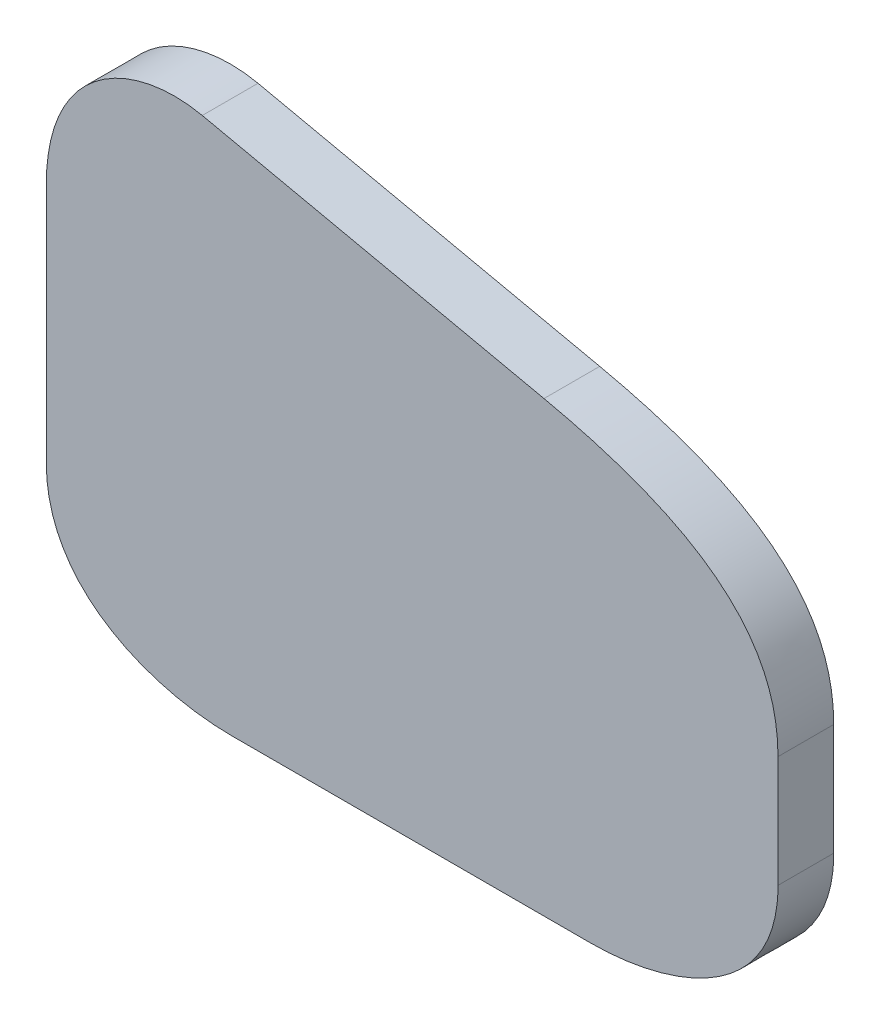
SolidWorks part; units mm, degrees
ref_plane "Спереди" through (0, 0, 0) normal (0, 0, 1) x (1, 0, 0)
ref_plane "Сверху" through (0, 0, 0) normal (0, 1, 0) x (1, 0, 0)
ref_plane "Справа" through (0, 0, 0) normal (1, 0, 0) x (0, 0, -1)
sketch "Эскиз1_fr" plane through (0, 0, 0) normal (0, 0, 1) x (1, 0, 0)
  line L0 (0, 0) -> (0, 20)
  line L1 (-41.9869, 54.6497) -> (-103.3012, 67.9789)
  line L2 (-131.2925, 43.0977) -> (-131.2925, 0)
  line L3 (-33.5451, -25.7698) -> (-97.9695, -25.7698)
  spline S0 degree 3 poles (0, 20) (0, 38.146) (-14.2095, 48.6111) (-41.9869, 54.6497) knots 0 0 0 0 1 1 1 1
  spline S1 degree 3 poles (-103.3012, 67.9789) (-115.5, 70.6308) (-131.2925, 63.3933) (-131.2925, 43.0977) knots 0 0 0 0 1 1 1 1
  spline S2 degree 3 poles (-33.5451, -25.7698) (-19.4449, -25.7698) (0, -19.0638) (0, 0) knots 0 0 0 0 1 1 1 1
  spline S3 degree 3 poles (-97.9695, -25.7698) (-112.0112, -25.7698) (-131.2925, -19.0252) (-131.2925, 0) knots 0 0 0 0 1 1 1 1
  dimension "D1" = 20
extrude "Бобышка-Вытянуть1" add sketch "Эскиз1_fr" along normal blind 10
sketch "Эскиз2_fr" plane through (0, 0, 0) normal (0, 0, -1) x (-1, 0, 0)
  line L0 (100.8084, 61.4805) -> (102.9069, 51.8273)
  line L1 (41.9869, 54.6497) -> (103.3012, 67.9789) construction
  line L2 (100.8084, 61.4805) -> (102.9069, 51.8273) construction
  line L3 (102.4293, 61.8329) -> (104.5278, 52.1796)
  line L4 (99.1876, 61.1282) -> (101.2861, 51.4749)
  arc A0 (102.4293, 61.8329) -> (99.1876, 61.1282) centre (100.8084, 61.4805) ccw
  arc A1 (101.2861, 51.4749) -> (104.5278, 52.1796) centre (102.9069, 51.8273) ccw
  point P4 (101.8577, 56.6539)
